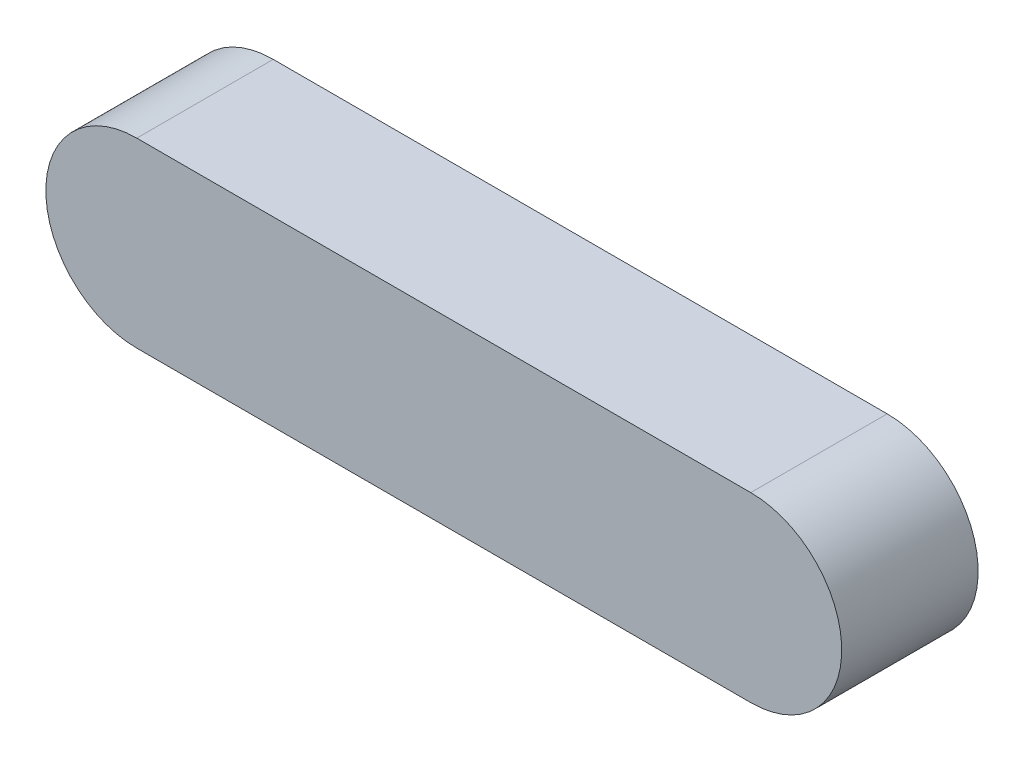
SolidWorks part; units mm, degrees
material "Plain Carbon Steel"
ref_plane "Front Plane" through (0, 0, 0) normal (0, 0, 1) x (1, 0, 0)
ref_plane "Top Plane" through (0, 0, 0) normal (0, 1, 0) x (1, 0, 0)
ref_plane "Right Plane" through (0, 0, 0) normal (1, 0, 0) x (0, 0, -1)
sketch "Sketch1" plane through (0, 0, 0) normal (0, 0, 1) x (1, 0, 0)
  line L0 (-27, 0) -> (27, 0) construction
  line L1 (-27, 8) -> (27, 8)
  line L2 (-27, -8) -> (27, -8)
  line L3 (-40.188, 0) -> (46.724, 0) construction
  line L4 (-35, 0) -> (-35, 16.5501) construction
  line L5 (35, 0) -> (35, 15.8403) construction
  arc A0 (-27, 8) -> (-27, -8) centre (-27, 0) ccw
  arc A1 (27, -8) -> (27, 8) centre (27, 0) ccw
  point P2 (0, 0)
  dimension "D2" = 8
  dimension "D1" = 70
extrude "Boss-Extrude1" add sketch "Sketch1" along normal blind 12
